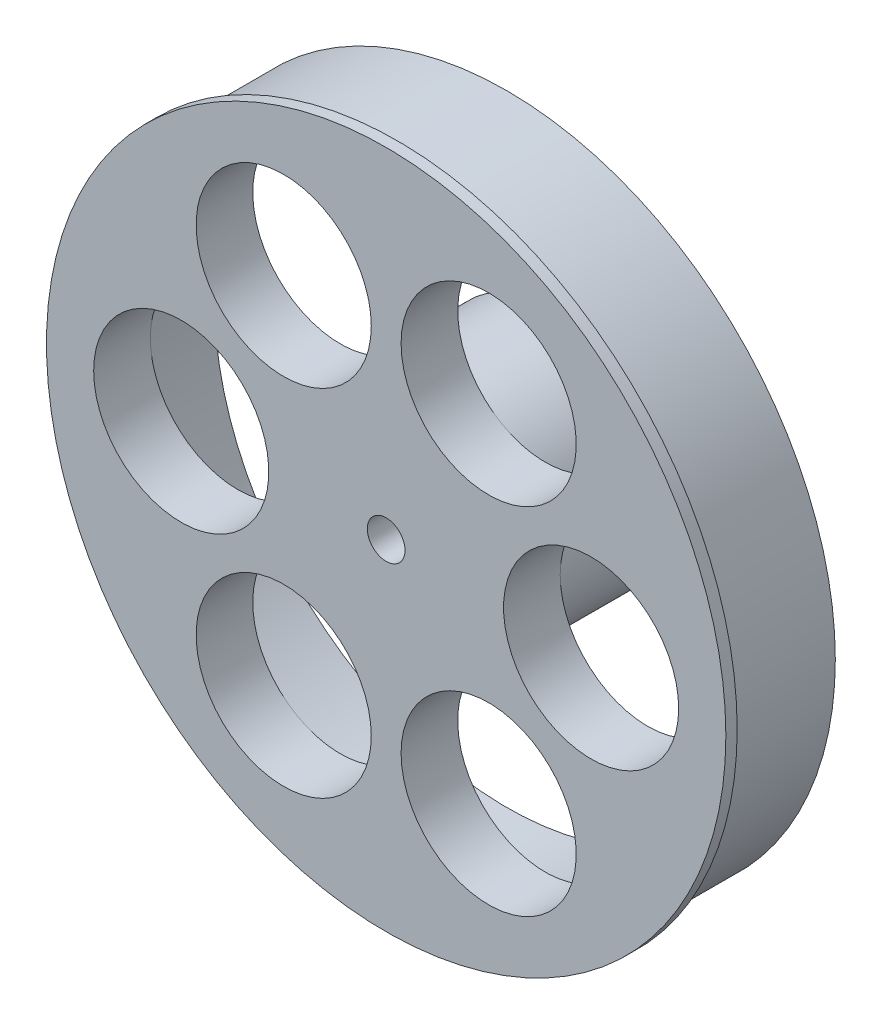
SolidWorks part; units mm, degrees
material "POM Acetal Copolymer"
ref_plane "Front Plane" through (0, 0, 0) normal (0, 0, 1) x (1, 0, 0)
ref_plane "Top Plane" through (0, 0, 0) normal (0, 1, 0) x (1, 0, 0)
ref_plane "Right Plane" through (0, 0, 0) normal (1, 0, 0) x (0, 0, -1)
sketch "Sketch1" plane through (0, 0, 0) normal (1, 0, 0) x (0, 0, -1)
  line L0 (-59.838, 0) -> (69.7594, 0) construction
  line L1 (1.5, 3.11) -> (4.4, 3.11)
  line L2 (0, 9) -> (0.3, 9)
  line L3 (0, 55) -> (0, -55) construction
  line L4 (3.2, 8.7) -> (3.2, 7.75)
  line L5 (3.2, 7.75) -> (1.5, 7.75)
  line L6 (1.5, 7.75) -> (1.5, 3.11)
  line L7 (4.4, 2.11) -> (2.3, 2.11)
  line L8 (0, 0.5) -> (0, 9)
  line L9 (4.4, 3.11) -> (4.4, 2.11)
  line L13 (0.3, 8.7) -> (0.3, 9)
  line L16 (3.2, 8.7) -> (0.3, 8.7)
  line L17 (2.3, 2.11) -> (2.3, 0.5)
  line L18 (2.3, 0.5) -> (0, 0.5)
  dimension "D1" = 4.22
  dimension "D2" = 18
  dimension "D3" = 15.5
  dimension "D4" = 1.2
  dimension "D5" = 0.3
  dimension "D6" = 1
  dimension "D7" = 1.5
  dimension "D8" = 0.3
  dimension "D9" = 3.2
  dimension "D10" = 1
  dimension "D11" = 2.1
revolve "Revolve1" add sketch "Sketch1" angle 360 about L0
sketch "Sketch2" plane through (0, 0, 0) normal (0, 0, 1) x (1, 0, 0)
  circle A0 centre (5.43, 0) radius 2.32
  circle A3 centre (0, 0) radius 3.11 construction
  circle A4 centre (0, 0) radius 7.75 construction
extrude "Cut-Extrude1" cut sketch "Sketch2" against normal up to next
pattern_circular "CirPattern1" count 6 over 360 about axis through (0, 0, 0) along (0, 0, 1) of "Cut-Extrude1"
